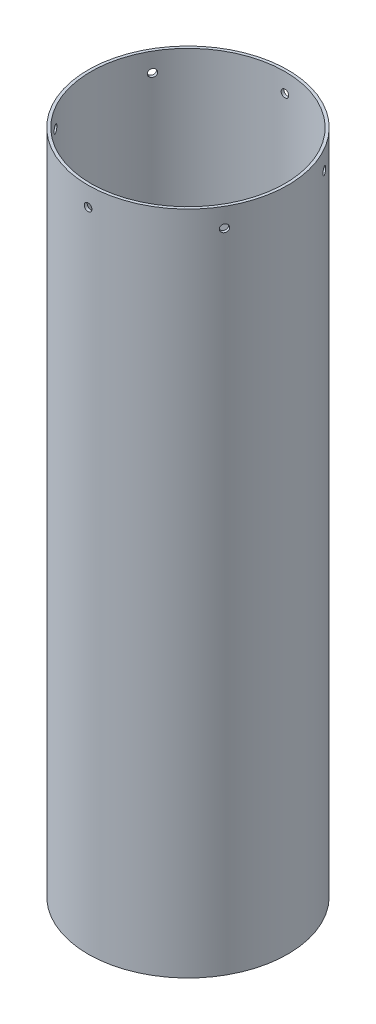
SolidWorks part; units mm, degrees
ref_plane "Спереди" through (0, 0, 0) normal (0, 0, 1) x (1, 0, 0)
ref_plane "Сверху" through (0, 0, 0) normal (0, 1, 0) x (1, 0, 0)
ref_plane "Справа" through (0, 0, 0) normal (1, 0, 0) x (0, 0, -1)
other "Configuration Table"
sketch "Эскиз1" plane through (0, 0, 0) normal (0, 1, 0) x (1, 0, 0)
  circle A0 centre (0, 0) radius 52.5
  circle A1 centre (0, 0) radius 51
  dimension "D1" = 105
  dimension "D2" = 102
extrude "Бобышка-Вытянуть1" add sketch "Эскиз1" along normal blind 350
sketch "Эскиз2" plane through (0, 0, 0) normal (0, 0, 1) x (1, 0, 0)
  line L0 (0, -1000) -> (0, 49000) construction
  line L1 (52.5, 350) -> (-52.5, 350) construction
  circle A0 centre (0, 340) radius 2
  dimension "D1" = 4
  dimension "D2" = 10
extrude "Вырез-Вытянуть1" cut sketch "Эскиз2" along normal blind 64
pattern_circular "Круговой массив1" count 6 over 360 about axis through (0, 350, 0) along (0, -1, 0) of "Вырез-Вытянуть1"
